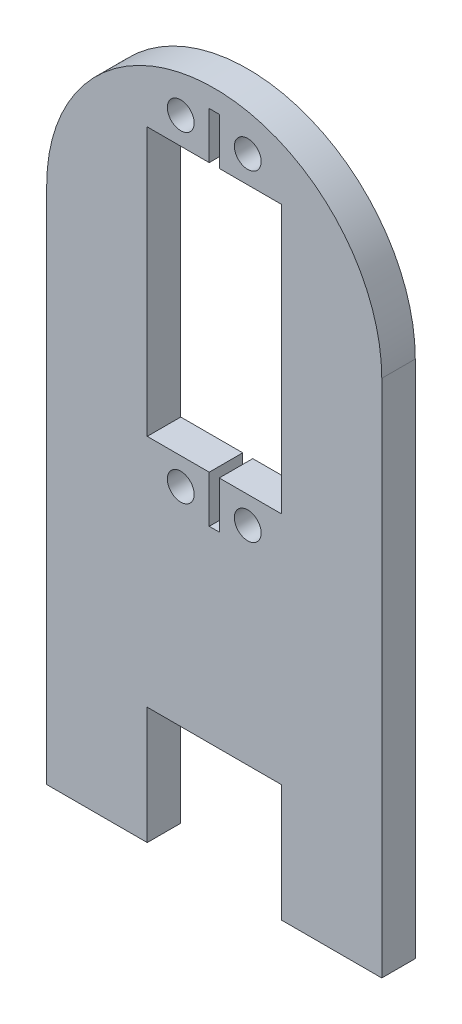
SolidWorks part; units mm, degrees
material "Balsa"
ref_plane "Front Plane" through (0, 0, 0) normal (0, 0, 1) x (1, 0, 0)
ref_plane "Top Plane" through (0, 0, 0) normal (0, 1, 0) x (1, 0, 0)
ref_plane "Right Plane" through (0, 0, 0) normal (1, 0, 0) x (0, 0, -1)
sketch "Sketch1" plane through (0, 0, 0) normal (0, 0, 1) x (1, 0, 0)
  line L0 (-10, 20) -> (10, 20)
  line L1 (-10, 20) -> (-10, -20)
  line L2 (-10, -20) -> (10, -20)
  line L3 (10, 20) -> (10, -20)
  line L4 (-10, 0) -> (10, 0) construction
  line L5 (-0.75, 27) -> (0.75, 27)
  line L6 (-0.75, 27) -> (-0.75, 20)
  line L7 (-0.75, 20) -> (0.75, 20)
  line L8 (0.75, 27) -> (0.75, 20)
  line L9 (-0.75, -27) -> (0.75, -27)
  line L10 (-0.75, -27) -> (-0.75, -20)
  line L11 (0.75, -27) -> (0.75, -20)
  line L13 (-25, 5) -> (25, 5)
  line L14 (-25, 5) -> (-25, -55)
  line L15 (-25, -55) -> (25, -55)
  line L16 (25, 5) -> (25, -55)
  line L17 (-25, -55) -> (-10, -55)
  line L18 (-25, -55) -> (-25, -65)
  line L19 (-25, -65) -> (-10, -65)
  line L20 (-10, -55) -> (-10, -65)
  line L21 (25, -55) -> (10, -55)
  line L22 (25, -55) -> (25, -65)
  line L23 (25, -65) -> (10, -65)
  line L24 (10, -55) -> (10, -65)
  line L25 (-10, -65) -> (-25, -65)
  line L26 (-10, -65) -> (-10, -72.5)
  line L27 (-10, -72.5) -> (-25, -72.5)
  line L28 (-25, -65) -> (-25, -72.5)
  line L29 (25, -65) -> (10, -65)
  line L30 (25, -65) -> (25, -72.5)
  line L31 (25, -72.5) -> (10, -72.5)
  line L32 (10, -65) -> (10, -72.5)
  circle A0 centre (-5, 24) radius 2
  circle A1 centre (5, 24) radius 2
  circle A2 centre (5, -24) radius 2
  circle A3 centre (-5, -24) radius 2
  arc A4 (25, 5) -> (-25, 5) centre (0, 5) ccw
  point P4 (0, 20)
  point P9 (0, 20)
  point P24 (0, 0)
  point P30 (0, -55)
  dimension "D6" = 4
  dimension "D7" = 4
  dimension "D1" = 20
  dimension "D2" = 40
  dimension "D3" = 7
  dimension "D4" = 1.5
  dimension "D5" = 10
  dimension "D8" = 5
  dimension "D9" = 24
  dimension "D10" = 50
  dimension "D11" = 60
  dimension "D12" = 55
  dimension "D13" = 15
  dimension "D14" = 15
  dimension "D15" = 10
  dimension "D16" = 7.5
  dimension "D17" = 7.5
extrude "Boss-Extrude1" add sketch "Sketch1" along normal blind 5 contours L16 L13 L14 L15 A2 A1 A0 L11 L9 L10 L2 L1 L0 L6 L5 L8 L3 A3 | L15 L24 L23 L22 | L20 L15 L18 L19 | L13 A4 | L26 L25 L28 L27 | L30 L29 L32 L31
